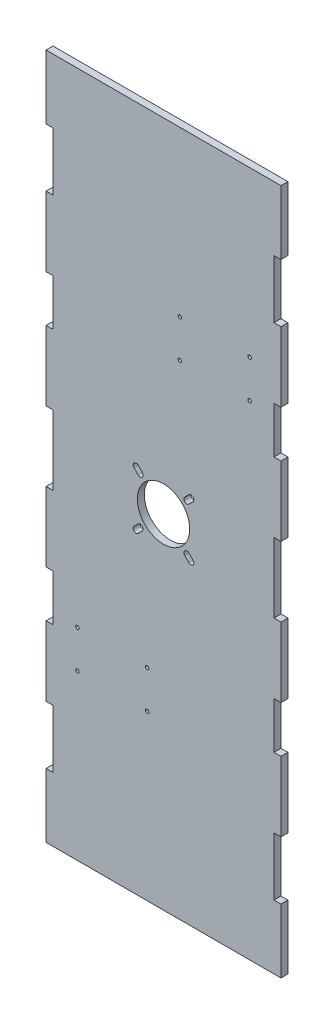
SolidWorks part; units mm, degrees
ref_plane "Front Plane" through (0, 0, 0) normal (0, 0, 1) x (1, 0, 0)
ref_plane "Top Plane" through (0, 0, 0) normal (0, 1, 0) x (1, 0, 0)
ref_plane "Right Plane" through (0, 0, 0) normal (1, 0, 0) x (0, 0, -1)
sketch "Sketch1" plane through (0, 0, 0) normal (0, 0, 1) x (1, 0, 0)
  line L0 (42.9176, -0.8355) -> (39.3794, 2.7028) construction
  line L1 (41.1498, -2.6032) -> (37.6116, 0.935)
  line L2 (44.6854, 0.9323) -> (41.1471, 4.4705)
  line L3 (-4.2248, -0.8355) -> (-0.6866, 2.7028) construction
  line L4 (-5.9926, 0.9323) -> (-2.4543, 4.4705)
  line L5 (-2.457, -2.6032) -> (1.0812, 0.935)
  line L6 (-4.2248, 46.3069) -> (-0.6866, 42.7687) construction
  line L7 (-2.457, 48.0747) -> (1.0812, 44.5365)
  line L8 (-5.9926, 44.5392) -> (-2.4543, 41.001)
  line L9 (42.9176, 46.3069) -> (39.3794, 42.7687) construction
  line L10 (44.6854, 44.5392) -> (41.1471, 41.001)
  line L11 (41.1498, 48.0747) -> (37.6116, 44.5365)
  line L32 (114.3464, -107.2643) -> (114.3464, -67.2643)
  line L34 (-81.6536, -272.336) -> (120.3464, -272.336)
  line L35 (-81.6536, -272.336) -> (-81.6536, -217.2643)
  line L36 (114.3464, 112.7357) -> (120.3464, 112.7357)
  line L39 (114.3464, 152.7357) -> (120.3464, 152.7357)
  line L40 (120.3464, 212.7357) -> (120.3464, 152.7357)
  line L42 (114.3464, 52.7357) -> (120.3464, 52.7357)
  line L43 (120.3464, 112.7357) -> (120.3464, 52.7357)
  line L44 (120.3464, -67.2643) -> (120.3464, -7.2643)
  line L45 (114.3464, -7.2643) -> (120.3464, -7.2643)
  line L47 (120.3464, -167.2643) -> (120.3464, -107.2643)
  line L48 (114.3464, -107.2643) -> (120.3464, -107.2643)
  line L51 (114.3464, -67.2643) -> (120.3464, -67.2643)
  line L52 (114.3464, 112.7357) -> (114.3464, 152.7357)
  line L53 (114.3464, -7.2643) -> (114.3464, 52.7357)
  line L54 (-75.6536, -7.2643) -> (-75.6536, 52.7357)
  line L55 (-75.6536, 112.7357) -> (-75.6536, 152.7357)
  line L56 (-75.6536, -67.2643) -> (-81.6536, -67.2643)
  line L58 (-75.6536, -107.2643) -> (-81.6536, -107.2643)
  line L59 (-81.6536, -167.2643) -> (-81.6536, -107.2643)
  line L60 (-75.6536, -7.2643) -> (-81.6536, -7.2643)
  line L61 (-81.6536, -67.2643) -> (-81.6536, -7.2643)
  line L62 (-81.6536, 112.7357) -> (-81.6536, 52.7357)
  line L63 (-75.6536, 52.7357) -> (-81.6536, 52.7357)
  line L65 (-75.6536, 152.7357) -> (-81.6536, 152.7357)
  line L67 (-75.6536, 112.7357) -> (-81.6536, 112.7357)
  line L68 (-75.6536, -107.2643) -> (-75.6536, -67.2643)
  line L69 (-81.6536, 152.7357) -> (-81.6536, 212.7357)
  line L73 (120.3464, -272.336) -> (120.3464, -217.2643)
  line L74 (-75.6536, 212.7357) -> (-75.6536, 262.7357)
  line L75 (120.3464, -167.2643) -> (114.3464, -167.2643)
  line L77 (120.3464, -217.2643) -> (114.3464, -217.2643)
  line L78 (114.3464, -167.2643) -> (114.3464, -217.2643)
  line L79 (-81.6536, -167.2643) -> (-75.6536, -167.2643)
  line L81 (-81.6536, -217.2643) -> (-75.6536, -217.2643)
  line L82 (-75.6536, -167.2643) -> (-75.6536, -217.2643)
  line L83 (-81.6536, 262.7357) -> (-75.6536, 262.7357)
  line L84 (114.3464, 212.7357) -> (114.3464, 262.7357)
  line L85 (120.3464, 262.7357) -> (114.3464, 262.7357)
  line L86 (120.3464, 317.8074) -> (120.3464, 262.7357)
  line L87 (-81.6536, 317.8074) -> (-81.6536, 262.7357)
  line L88 (-81.6536, 317.8074) -> (120.3464, 317.8074)
  line L89 (-81.6536, 212.7357) -> (-75.6536, 212.7357)
  line L90 (114.3464, 212.7357) -> (120.3464, 212.7357)
  circle A0 centre (93.4214, 144.1872) radius 1.5
  circle A1 centre (93.4214, 176.6664) radius 1.5
  circle A2 centre (33.4214, 144.1872) radius 1.5
  circle A8 centre (-54.7286, -131.1949) radius 1.5
  arc A9 (41.1498, -2.6032) -> (44.6854, 0.9323) centre (42.9176, -0.8355) ccw
  arc A10 (41.1471, 4.4705) -> (37.6116, 0.935) centre (39.3794, 2.7028) ccw
  circle A11 centre (33.4214, 176.6664) radius 1.5
  arc A12 (-5.9926, 0.9323) -> (-2.457, -2.6032) centre (-4.2248, -0.8355) ccw
  arc A13 (1.0812, 0.935) -> (-2.4543, 4.4705) centre (-0.6866, 2.7028) ccw
  arc A14 (-2.457, 48.0747) -> (-5.9926, 44.5392) centre (-4.2248, 46.3069) ccw
  arc A15 (-2.4543, 41.001) -> (1.0812, 44.5365) centre (-0.6866, 42.7687) ccw
  arc A16 (44.6854, 44.5392) -> (41.1498, 48.0747) centre (42.9176, 46.3069) ccw
  arc A17 (37.6116, 44.5365) -> (41.1471, 41.001) centre (39.3794, 42.7687) ccw
  circle A18 centre (-54.7286, -98.7157) radius 1.5
  circle A20 centre (5.2714, -98.7157) radius 1.5
  circle A21 centre (19.3464, 22.7357) radius 22.5118
  circle A22 centre (5.2714, -131.1949) radius 1.5
  point P28 (41.1485, 0.9337)
  point P33 (-2.4557, 0.9337)
  point P40 (-2.4557, 44.5378)
  point P47 (41.1485, 44.5378)
  point P52 (19.3464, 22.7357)
  point P91 (19.3464, 22.7357)
  dimension "D6" = 2
  dimension "D2" = 4
extrude "Boss-Extrude1" add sketch "Sketch1" along normal blind 6
sketch "Sketch2" plane through (120.3464, 0, 0) normal (1, 0, 0) x (0, 0, -1)
  line L1 (0, -272.336) -> (80, -272.336)
  line L2 (0, -272.336) -> (0, -217.2643)
  line L3 (0, 317.8074) -> (80, 317.8074)
  line L4 (80, -272.336) -> (80, 317.8074)
  line L5 (0, -167.2643) -> (0, -107.2643)
  line L6 (0, 262.7357) -> (-6, 262.7357)
  line L8 (0, 212.7357) -> (-6, 212.7357)
  line L9 (-6, 262.7357) -> (-6, 212.7357)
  line L10 (0, 152.7357) -> (-6, 152.7357)
  line L12 (0, 112.7357) -> (-6, 112.7357)
  line L13 (-6, 152.7357) -> (-6, 112.7357)
  line L14 (0, 52.7357) -> (-6, 52.7357)
  line L16 (0, -7.2643) -> (-6, -7.2643)
  line L17 (-6, 52.7357) -> (-6, -7.2643)
  line L18 (-6, -107.2643) -> (0, -107.2643)
  line L19 (-6, -107.2643) -> (-6, -67.2643)
  line L20 (-6, -67.2643) -> (0, -67.2643)
  line L22 (0, -217.2643) -> (-6, -217.2643)
  line L24 (0, -167.2643) -> (-6, -167.2643)
  line L25 (-6, -217.2643) -> (-6, -167.2643)
  line L26 (0, -67.2643) -> (0, -7.2643)
  line L27 (0, 52.7357) -> (0, 112.7357)
  line L28 (0, 152.7357) -> (0, 212.7357)
  line L29 (0, 262.7357) -> (0, 317.8074)
  dimension "D1" = 80
